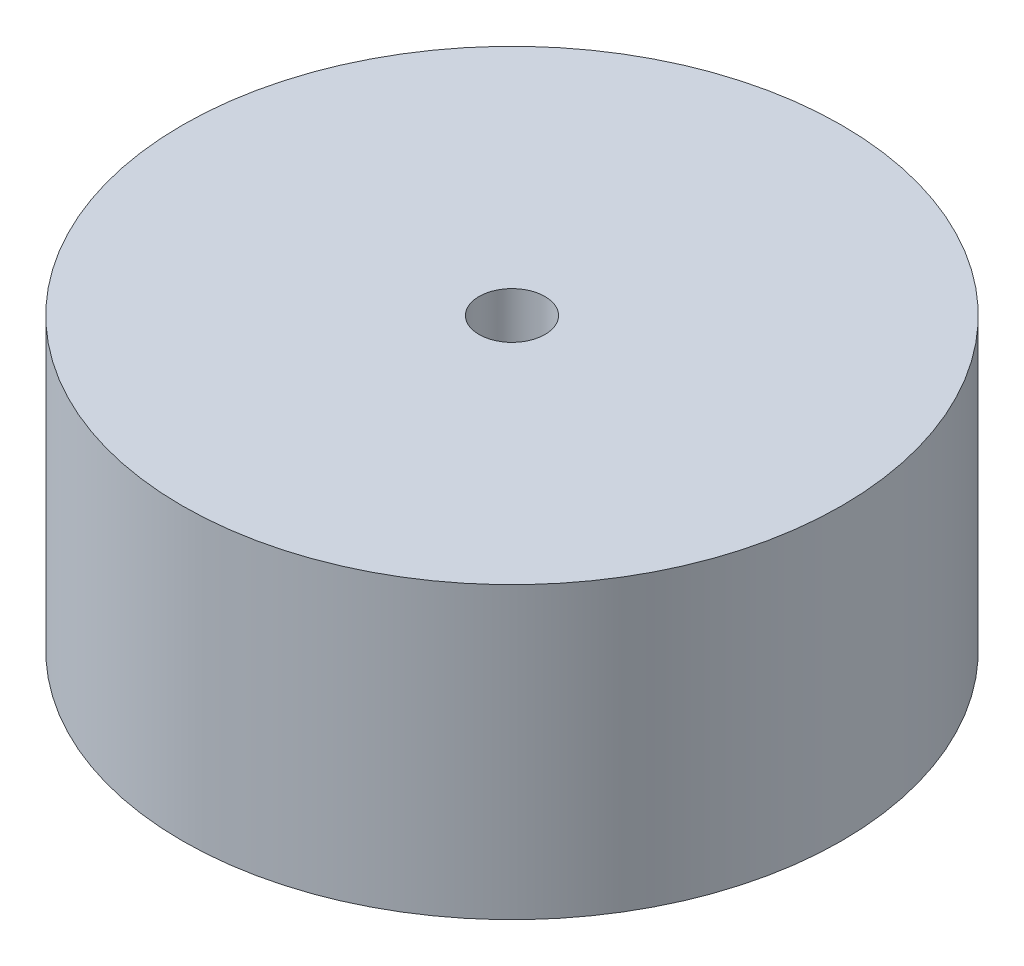
SolidWorks part; units mm, degrees
ref_plane "前视基准面" through (0, 0, 0) normal (0, 0, 1) x (1, 0, 0)
ref_plane "上视基准面" through (0, 0, 0) normal (0, 1, 0) x (1, 0, 0)
ref_plane "右视基准面" through (0, 0, 0) normal (1, 0, 0) x (0, 0, -1)
sketch "草图1" plane through (0, 0, 0) normal (0, 1, 0) x (1, 0, 0)
  line L0 (0, 0) -> (0, 50000) construction
  line L1 (0, 0) -> (50000, 0) construction
  circle A0 centre (0, 0) radius 50
extrude "凸台-拉伸3" add sketch "草图1" along normal blind 45
sketch "草图5" plane through (0, 0, 0) normal (0, -1, 0) x (1, 0, 0)
  line L0 (0, 0) -> (0, 50000) construction
  line L1 (0, 0) -> (50000, 0) construction
  circle A0 centre (0, 0) radius 5
extrude "切除-拉伸1" cut sketch "草图5" against normal through all
sketch "草图6" plane through (0, 45, 0) normal (0, 1, 0) x (1, 0, 0)
  circle A0 centre (0, 0) radius 50
extrude "切除-拉伸2" cut sketch "草图6" against normal blind 5
scale "缩放比例3" bodies to scale 107 scale about centroid uniform scaling yes scale factor 0.5
scale "缩放比例4" bodies to scale 110 scale about centroid uniform scaling yes scale factor 1.2
sketch "草图7" plane through (0, 32, 0) normal (0, 1, 0) x (1, 0, 0)
  circle A0 centre (0, 0) radius 3
  circle A1 centre (0, 0) radius 30
extrude "凸台-拉伸4" add sketch "草图7" along normal blind 2.4
